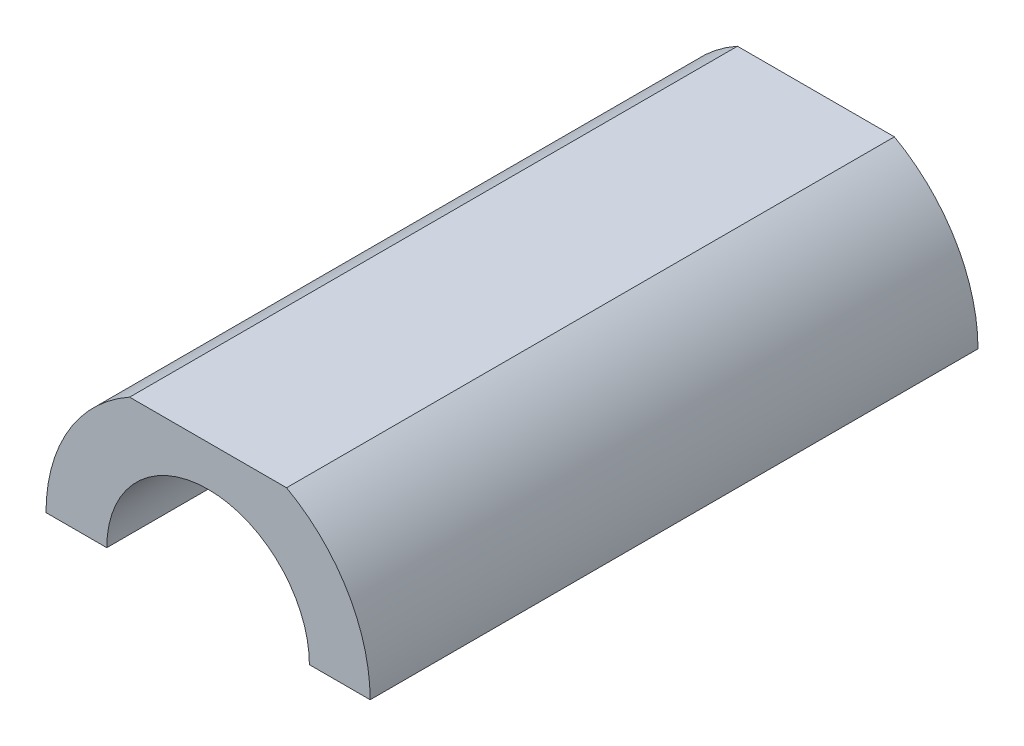
SolidWorks part; units mm, degrees
ref_plane "Alzado" through (0, 0, 0) normal (0, 0, 1) x (1, 0, 0)
ref_plane "Planta" through (0, 0, 0) normal (0, 1, 0) x (1, 0, 0)
ref_plane "Vista lateral" through (0, 0, 0) normal (1, 0, 0) x (0, 0, -1)
sketch "Croquis1" plane through (0, 0, 0) normal (0, 0, 1) x (1, 0, 0)
  line L0 (-8, 0) -> (-5, 0)
  line L2 (5, 0) -> (8, 0)
  line L4 (3.873, 7) -> (-3.873, 7)
  arc A0 (5, 0) -> (-5, 0) centre (0, 0) ccw
  arc A2 (-8, 0) -> (-3.873, 7) centre (0, 0) cw
  arc A3 (3.873, 7) -> (8, 0) centre (0, 0) cw
extrude "Saliente-Extruir1" add sketch "Croquis1" along normal blind 30
